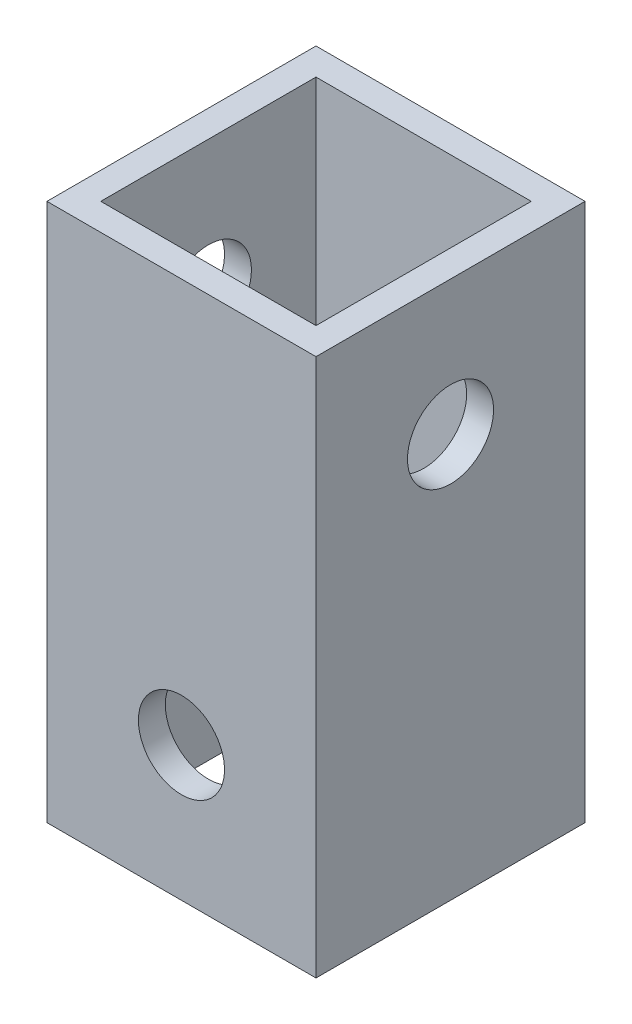
SolidWorks part; units mm, degrees
ref_plane "正面" through (0, 0, 0) normal (0, 0, 1) x (1, 0, 0)
ref_plane "平面" through (0, 0, 0) normal (0, 1, 0) x (1, 0, 0)
ref_plane "右側面" through (0, 0, 0) normal (1, 0, 0) x (0, 0, -1)
sketch "ｽｹｯﾁ1" plane through (0, 0, 0) normal (0, 1, 0) x (1, 0, 0)
  line L0 (-4, 4) -> (4, 4)
  line L1 (-5, 5) -> (5, 5)
  line L2 (-5, 5) -> (-5, -5)
  line L3 (-5, -5) -> (5, -5)
  line L4 (5, 5) -> (5, -5)
  line L5 (-5, 5) -> (5, -5) construction
  line L6 (-5, -5) -> (5, 5) construction
  line L7 (4, 4) -> (4, -4)
  line L8 (-4, -4) -> (4, -4)
  line L9 (-4, 4) -> (-4, -4)
  point P0 (0, 0)
  dimension "D1" = 10
  dimension "D2" = 10
  dimension "D3" = 1
extrude "ﾎﾞｽ - 押し出し1" add sketch "ｽｹｯﾁ1" along normal blind 20
sketch "ｽｹｯﾁ2" plane through (0, 0, -5) normal (0, 0, -1) x (-1, 0, 0)
  line L0 (-5, 0) -> (5, 0) construction
  circle A0 centre (0, 5) radius 1.6
  dimension "D1" = 5
extrude "ｶｯﾄ - 押し出し1" cut sketch "ｽｹｯﾁ2" against normal blind 20
sketch "ｽｹｯﾁ3" plane through (-5, 0, 0) normal (-1, 0, 0) x (0, 0, 1)
  line L0 (-5, 0) -> (5, 0) construction
  circle A0 centre (0, 15) radius 1.6
  dimension "D1" = 15
  dimension "D2" = 3.2
extrude "ｶｯﾄ - 押し出し2" cut sketch "ｽｹｯﾁ3" against normal blind 20
